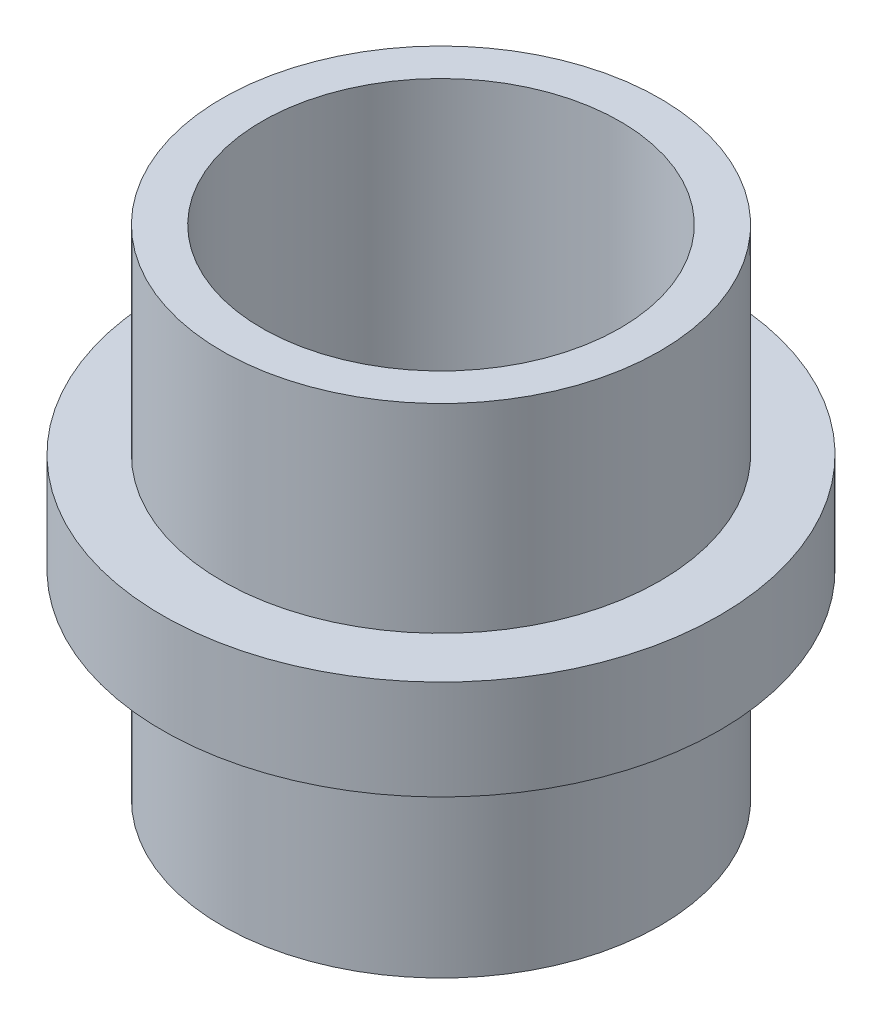
SolidWorks part; units mm, degrees
ref_plane "Front Plane" through (0, 0, 0) normal (0, 0, 1) x (1, 0, 0)
ref_plane "Top Plane" through (0, 0, 0) normal (0, 1, 0) x (1, 0, 0)
ref_plane "Right Plane" through (0, 0, 0) normal (1, 0, 0) x (0, 0, -1)
sketch "Sketch1" plane through (0, 0, 0) normal (0, 0, 1) x (1, 0, 0)
  line L9 (0, -12.5) -> (0, 12.5) construction
  line L10 (9, 12.5) -> (11, 12.5)
  line L11 (11, 12.5) -> (11, 2.5)
  line L12 (11, 2.5) -> (14, 2.5)
  line L13 (14, 2.5) -> (14, -2.5)
  line L14 (14, -2.5) -> (11, -2.5)
  line L15 (11, -2.5) -> (11, -12.5)
  line L16 (11, -12.5) -> (9, -12.5)
  line L17 (9, -12.5) -> (9, 12.5)
  point P4 (0, 0)
  point P10 (0, 0)
  point P12 (0, 0)
  point P13 (5.506, -12.588)
  point P14 (0, 0)
  point P15 (3.9646, 12.5)
  point P16 (0, 0)
  point P18 (14, 0)
  dimension "D1" = 25
  dimension "D2" = 2
  dimension "D3" = 11
  dimension "D4" = 14
  dimension "D5" = 5
revolve "Revolve1" add sketch "Sketch1" angle 360 about L9
